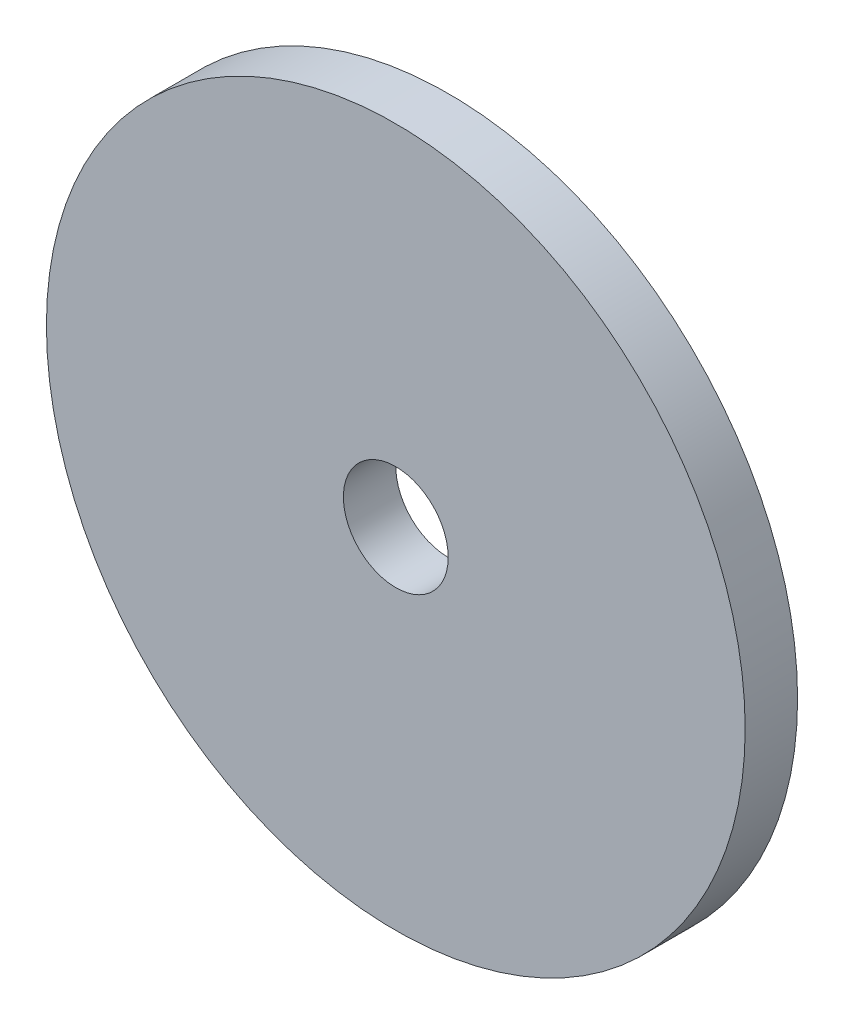
SolidWorks part; units mm, degrees
ref_plane "前视" through (0, 0, 0) normal (0, 0, 1) x (1, 0, 0)
ref_plane "上视" through (0, 0, 0) normal (0, 1, 0) x (1, 0, 0)
ref_plane "右视" through (0, 0, 0) normal (1, 0, 0) x (0, 0, -1)
sketch "草图1" plane through (0, 0, 0) normal (0, 0, 1) x (1, 0, 0)
  circle A0 centre (0, 0) radius 40
  circle A1 centre (0, 0) radius 6
  dimension "D1" = 80
  dimension "D2" = 12
extrude "凸台-拉伸1" add sketch "草图1" along normal blind 6 contours A0 A1
